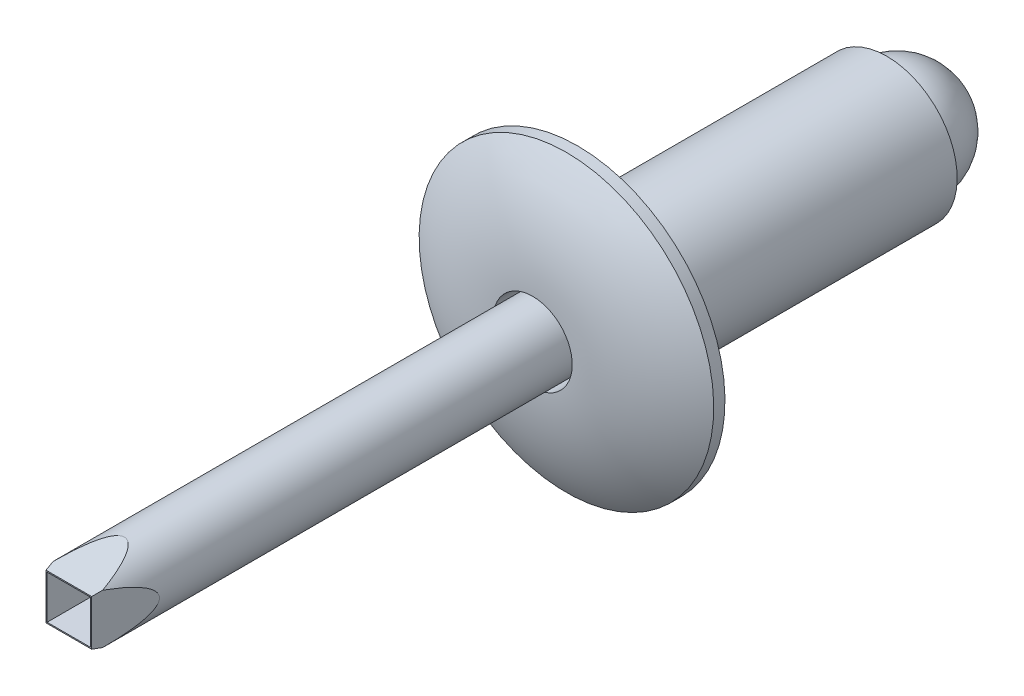
SolidWorks part; units mm, degrees
material "5052-O"
ref_plane "Front" through (0, 0, 0) normal (0, 0, 1) x (1, 0, 0)
ref_plane "Top" through (0, 0, 0) normal (0, 1, 0) x (1, 0, 0)
ref_plane "Right" through (0, 0, 0) normal (1, 0, 0) x (0, 0, -1)
sketch "Sketch1" plane through (0, 0, 0) normal (1, 0, 0) x (0, 0, -1)
  line L0 (-11.4935, 0) -> (-1.016, 0) construction
  line L1 (-1.016, 0) -> (0, 0) construction
  line L2 (0, 0) -> (6.985, 0) construction
  line L3 (6.985, 0) -> (8.509, 0) construction
  line L8 (0, 3.3274) -> (0, -3.3274) construction
  line L9 (6.985, 1.5875) -> (6.985, -1.5875) construction
  dimension "Length" = 6.985
  dimension "Head Height" = 1.016
  dimension "D5" = 1.524
  dimension "D9" = 10.4775
  dimension "Diameter" = 3.175
  dimension "Head Diameter" = 6.6548
sketch "Sketch2" plane through (0, 0, 0) normal (1, 0, 0) x (0, 0, -1)
  line L0 (-11.4935, 0.7937) -> (-11.4935, 0) construction
  line L1 (-11.4935, 0.7937) -> (0, 0.7937) construction
  line L2 (0, 3.3274) -> (0, -3.3274) construction
  line L3 (0, 0) -> (0, 3.3274) construction
  line L4 (-1.016, 0) -> (-1.016, -1.8472) construction
  line L5 (6.985, 1.5875) -> (0, 1.5875)
  line L6 (6.985, 1.5875) -> (6.985, 0) construction
  line L7 (8.509, 0) -> (8.509, 1.5875) construction
  line L8 (6.985, 1.5875) -> (6.985, 0)
  line L9 (8.509, 1.5875) -> (6.985, 1.5875) construction
  line L11 (6.985, 0) -> (8.509, 0) construction
  line L12 (6.985, 0) -> (0.6985, 0)
  line L13 (-1.016, 0.7937) -> (-1.016, 0) construction
  line L14 (6.985, 1.5875) -> (6.985, 0) construction
  line L15 (6.985, 1.5875) -> (6.985, 0) construction
  line L16 (6.985, 0) -> (6.985, 1.5875) construction
  line L17 (6.985, 1.5875) -> (6.985, 0) construction
  line L18 (6.985, 0) -> (6.985, 1.5875) construction
  line L19 (0, 1.5875) -> (0, 3.3274)
  line L20 (-1.016, 0.893) -> (0, 0.893)
  line L21 (-11.4935, 0.893) -> (0, 0.893) construction
  line L22 (0, 3.3274) -> (-0.254, 3.3274)
  line L23 (0, 0.893) -> (0.6985, 0.893)
  line L24 (0.6985, 0.893) -> (0.6985, 0)
  arc A0 (8.509, 0) -> (6.985, 1.27) centre (7.2178, 0) ccw construction
  arc A2 (-0.254, 3.3274) -> (-1.016, 0.893) centre (3.2538, 0.893) ccw
  dimension "D3" = 0.254
  dimension "D1" = 0.7937
  dimension "D2" = 0.6985
  dimension "D5" = 1.27
  dimension "D4" = 0.0992
revolve "Revolve1" add sketch "Sketch2" angle 360 about L12
sketch "Sketch7" plane through (0, 0, 0) normal (1, 0, 0) x (0, 0, -1)
  line L0 (-11.4935, 0.7937) -> (0.6985, 0.7937)
  line L1 (0.6985, 0.893) -> (0.6985, 0) construction
  line L2 (0.6985, 0.7937) -> (0.6985, 0)
  line L3 (0.6985, 0) -> (-11.4935, 0)
  line L4 (-11.4935, 0) -> (-11.4935, 0.7937)
revolve "Revolve2" add sketch "Sketch7" angle 360 about L0
sketch "Sketch8" plane through (0, 0, 0) normal (1, 0, 0) x (0, 0, -1)
  line L1 (6.985, 1.27) -> (6.985, 0)
  line L2 (6.985, 0) -> (8.509, 0)
  arc A0 (8.509, 0) -> (6.985, 1.27) centre (7.2178, 0) ccw construction
  arc A1 (8.509, 0) -> (6.985, 1.27) centre (7.2178, 0) ccw
revolve "Revolve3" add sketch "Sketch8" angle 360 about L3
sketch "Sketch3" plane through (0, 0, 0) normal (0, 1, 0) x (1, 0, 0)
  line L0 (-0.997, -9.3238) -> (-0.5159, -11.4935)
  line L2 (-0.7937, -11.4935) -> (0.7937, -11.4935) construction
  line L3 (0, -11.4935) -> (0, -12.0015) construction
  line L4 (-0.5159, -11.4935) -> (0.5159, -11.4935)
  line L5 (-0.997, -9.3238) -> (-0.997, -12.0015)
  line L6 (-0.997, -12.0015) -> (0.9969, -12.0015)
  line L7 (0.9969, -12.0015) -> (0.9969, -9.3238)
  line L8 (-0.7937, 0.6985) -> (-0.7937, -11.4935) construction
  line L9 (0, -11.4935) -> (0, -1.016) construction
  line L10 (0.5159, -11.4935) -> (0.9969, -9.3238)
  point P12 (0, -11.4935)
  dimension "D3" = 0.508
  dimension "D2" = 0.2032
  dimension "D1" = 25
  dimension "D4" = 1.0319
extrude "Cut-Extrude1" cut sketch "Sketch3" against normal through all both and the other way through all
pattern_circular "CirPattern1" count 2 every 90 about axis through (0, 0, 11.4935) along (0, 0, -1) of "Cut-Extrude1"
sketch "Sketch9" plane through (0, 0, 11.4935) normal (0, 0, 1) x (1, 0, 0)
  line L8 (-0.4905, -0.4905) -> (0.4905, -0.4905)
  line L9 (0.4905, -0.4905) -> (0.4905, 0.4905)
  line L10 (0.4905, 0.4905) -> (-0.4905, 0.4905)
  line L11 (-0.4905, 0.4905) -> (-0.4905, -0.4905)
  line L12 (-0.4905, -0.4905) -> (0.4905, -0.4905)
  line L13 (0.4905, -0.4905) -> (0.4905, 0.4905)
  line L14 (0.4905, 0.4905) -> (-0.4905, 0.4905)
  line L15 (-0.4905, 0.4905) -> (-0.4905, -0.4905)
  dimension "D1" = 0.0254
extrude "Cut-Extrude3" cut sketch "Sketch9" against normal blind 2.54
fillet "Fillet2" radius 0.254 1 edges at (0, 1.5875, 0)
ref_plane "Contact Plane 1" through (0, 0, 0) normal (0, 0, -1) x (-1, 0, 0)
equation "\"D5@Sketch1\" = \"Head Height@Sketch1\" * 1.5"
equation "\"D9@Sketch1\" = \"Length@Sketch1\" * 1.5"
equation "\"D1@Sketch2\"=\"Diameter@Sketch1\"/4"
equation "\"D4@Sketch2\"=\"D1@Sketch2\"/8"
equation "\"D2@Sketch2\"=\"Length@Sketch1\"/10"
equation "\"D4@Sketch3\"=\"D1@Sketch2\"*2*.65"
equation "\"D5@Sketch2\"=\"Diameter@Sketch1\"*.8/2"
